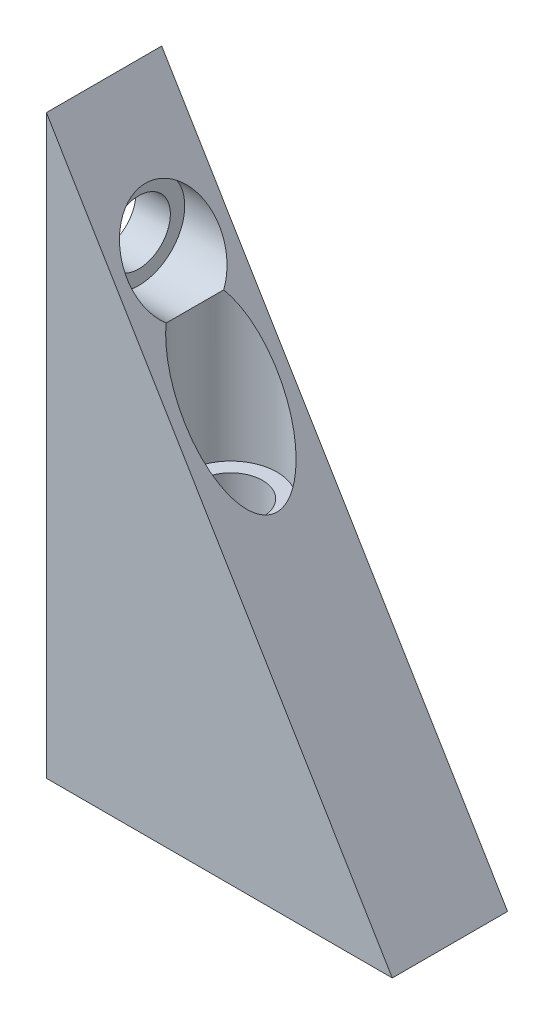
SolidWorks part; units mm, degrees
ref_plane "前视基准面" through (0, 0, 0) normal (0, 0, 1) x (1, 0, 0)
ref_plane "上视基准面" through (0, 0, 0) normal (0, 1, 0) x (1, 0, 0)
ref_plane "右视基准面" through (0, 0, 0) normal (1, 0, 0) x (0, 0, -1)
other "Configuration Table"
sketch "草图1" plane through (0, 0, 0) normal (0, 0, 1) x (1, 0, 0)
  line L0 (0, 0) -> (0, 50)
  line L1 (0, 50) -> (30, 0)
  line L2 (30, 0) -> (0, 0)
  dimension "D1" = 30
  dimension "D2" = 50
extrude "凸台-拉伸1" add sketch "草图1" along normal blind 10
sketch "草图2" plane through (0, 0, 0) normal (0, -1, 0) x (1, 0, 0)
  line L0 (-1.5872, 5) -> (31.4284, 5) construction
  line L1 (0, 0) -> (30, 0) construction
  line L2 (0, 10) -> (30, 10) construction
  line L3 (0, 10) -> (0, 0) construction
  circle A0 centre (11, 5) radius 2.75
  dimension "D2" = 5.5
  dimension "D1" = 11
extrude "切除-拉伸1" cut sketch "草图2" against normal through all
sketch "草图3" plane through (0, 0, 0) normal (-1, 0, 0) x (0, 0, 1)
  line L0 (5, -1.8108) -> (5, 51.5968) construction
  line L1 (10, 50) -> (10, 0) construction
  line L2 (0, 50) -> (0, 0) construction
  line L3 (10, 0) -> (0, 0) construction
  circle A0 centre (5, 40) radius 2.75
  dimension "D2" = 5.5
  dimension "D1" = 40
extrude "切除-拉伸2" cut sketch "草图3" against normal through all
ref_plane "基准面1" through (0, 50, 0) normal (0, -1, 0) x (-1, 0, 0)
sketch "草图4" plane through (0, 50, 0) normal (0, -1, 0) x (-1, 0, 0)
  circle A0 centre (-11, -5) radius 4
  dimension "D1" = 8
extrude "切除-拉伸3" cut sketch "草图4" along normal blind 26
ref_plane "基准面2" through (30, 0, 0) normal (-1, 0, 0) x (0, 0, 1)
sketch "草图5" plane through (30, 0, 0) normal (-1, 0, 0) x (0, 0, 1)
  circle A0 centre (5, 40) radius 4
  dimension "D1" = 8
extrude "切除-拉伸4" cut sketch "草图5" along normal blind 27
